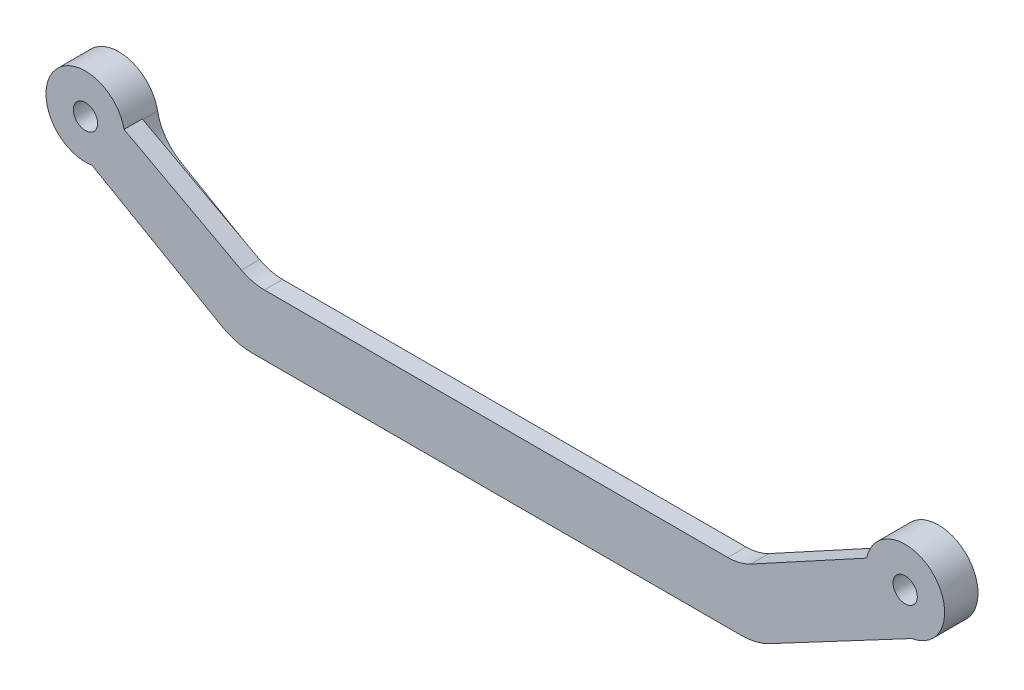
SolidWorks part; units mm, degrees
ref_plane "前视基准面" through (0, 0, 0) normal (0, 0, 1) x (1, 0, 0)
ref_plane "上视基准面" through (0, 0, 0) normal (0, 1, 0) x (1, 0, 0)
ref_plane "右视基准面" through (0, 0, 0) normal (1, 0, 0) x (0, 0, -1)
ref_plane "基准面1" through (0, 0, 5.5) normal (0, 0, 1) x (1, 0, 0)
sketch "草图1" plane through (0, 0, 5.5) normal (0, 0, 1) x (1, 0, 0)
  line L0 (-41.12, -13.8584) -> (41.12, -13.8584)
  line L1 (-41.92, -16.8584) -> (41.92, -16.8584)
  line L2 (41.12, -13.8584) -> (61.27, -2.2316)
  line L3 (41.92, -16.8584) -> (62.7647, -4.8184)
  line L4 (-41.12, -13.8584) -> (-61.27, -2.2139)
  line L5 (-41.92, -16.8584) -> (-62.77, -4.8184)
  arc A0 (62.7647, -4.8184) -> (61.27, -2.2316) centre (67.4947, -0.36) ccw
  arc A1 (-61.27, -2.2139) -> (-62.77, -4.8184) centre (-67.5, -0.36) ccw
  point P6 (-66.8426, 0)
  point P13 (0, -13.8584)
  dimension "D1" = 13
  dimension "D2" = 13
  dimension "D3" = 12.04
  dimension "D4" = 3
  dimension "D5" = 4.73
  dimension "D6" = 6.23
  dimension "D7" = 25.58
  dimension "D8" = 26.38
  dimension "D9" = 108.62
  dimension "D10" = 109.42
  dimension "D11" = 128.77
  dimension "D12" = 4.73
  dimension "D13" = 12.04
  dimension "D14" = 134.9947
extrude "凸台-拉伸2" add sketch "草图1" along normal blind 2.5
sketch "草图4" plane through (0, 0, 8) normal (0, 0, 1) x (1, 0, 0)
  line L0 (-61.14, 0.9818) -> (-40.05, -10.3584)
  line L1 (-40.05, -10.3584) -> (40.31, -10.3584)
  line L2 (40.31, -10.3584) -> (61.1347, 0.9818)
  line L3 (-66.4125, -6.7684) -> (-42.73, -20.3584)
  line L4 (-42.73, -20.3584) -> (42.99, -20.3584)
  line L5 (42.99, -20.3584) -> (68.5822, -6.7684)
  line L6 (41.12, -13.8584) -> (-41.12, -13.8584) construction
  arc A2 (62.7647, -4.8184) -> (61.27, -2.2316) centre (67.4947, -0.36) ccw construction
  arc A3 (68.5822, -6.7684) -> (61.1347, 0.9818) centre (67.4947, -0.36) ccw
  arc A5 (-61.27, -2.2139) -> (-62.77, -4.8184) centre (-67.5, -0.36) ccw construction
  arc A6 (-61.14, 0.9818) -> (-66.4125, -6.7684) centre (-67.5, -0.36) ccw
  point P1 (-61.14, 0.4296)
  point P2 (-66.3868, -6.764)
  point P12 (0, 0)
  point P15 (0, 0)
  point P16 (0, 0)
  point P19 (67.6364, -0.5605)
  point P20 (67.6364, -0.5605)
  point P21 (-61.0242, -0.5605)
  point P22 (-67.64, -0.5605)
  point P23 (0, 0)
  point P24 (0, 0)
  point P25 (0, 0)
  point P26 (0, 0)
  point P27 (0, 0)
  point P28 (0, 0)
  point P29 (-67.5331, 0)
  point P30 (-67.5, -6.7684)
  point P31 (-61.14, 1.2384)
  point P32 (-65.4859, -6.7684)
  point P33 (-66.3008, -6.5)
  point P34 (-64.7581, -6.7684)
  point P35 (0, 0)
  point P36 (-67.3812, -0.3845)
  point P37 (-67.5298, -2.1628)
  point P38 (-67.64, -2.7556)
  point P42 (-66.4125, -6.7684)
  point P43 (-66.4125, -6.7684)
  point P44 (-61.1446, 1.0032)
  point P45 (-61.14, 0.9818)
  point P46 (-66.4083, -6.7684)
  point P47 (-66.4056, -6.7684)
  point P49 (61.27, 0.9818)
  point P50 (67.4947, -6.86)
  point P51 (61.1347, 0.9818)
  point P52 (-66.4473, -6.7684)
  point P53 (0, 0)
  dimension "D2" = 14.8402
  dimension "D4" = 18.41
  dimension "D5" = 21.09
  dimension "D6" = 3.5
  dimension "D7" = 7.09
  dimension "D8" = 6.5
  dimension "D9" = 101.45
  dimension "D10" = 104.13
extrude "凸台-拉伸3" add sketch "草图4" along normal blind 3
sketch "草图5" plane through (0, 0, 11) normal (0, 0, 1) x (1, 0, 0)
  circle A2 centre (67.4947, -0.36) radius 2
  circle A5 centre (-67.5, -0.36) radius 2
extrude "切除-拉伸1" cut sketch "草图5" against normal through all both and the other way through all
fillet "圆角1" radius 10 4 edges at (-42.73, -20.3584, 9.5) (-41.92, -16.8584, 6.75) (42.99, -20.3584, 9.5) (41.92, -16.8584, 6.75)
fillet "圆角2" radius 8 4 edges at (-61.27, -2.2139, 6.75) (-62.77, -4.8184, 6.75) (62.7647, -4.8184, 6.75) (61.27, -2.2316, 6.75)
fillet "圆角3" radius 8 4 edges at (40.31, -10.3584, 9.5) (41.12, -13.8584, 6.75) (-41.12, -13.8584, 6.75) (-40.05, -10.3584, 9.5)
